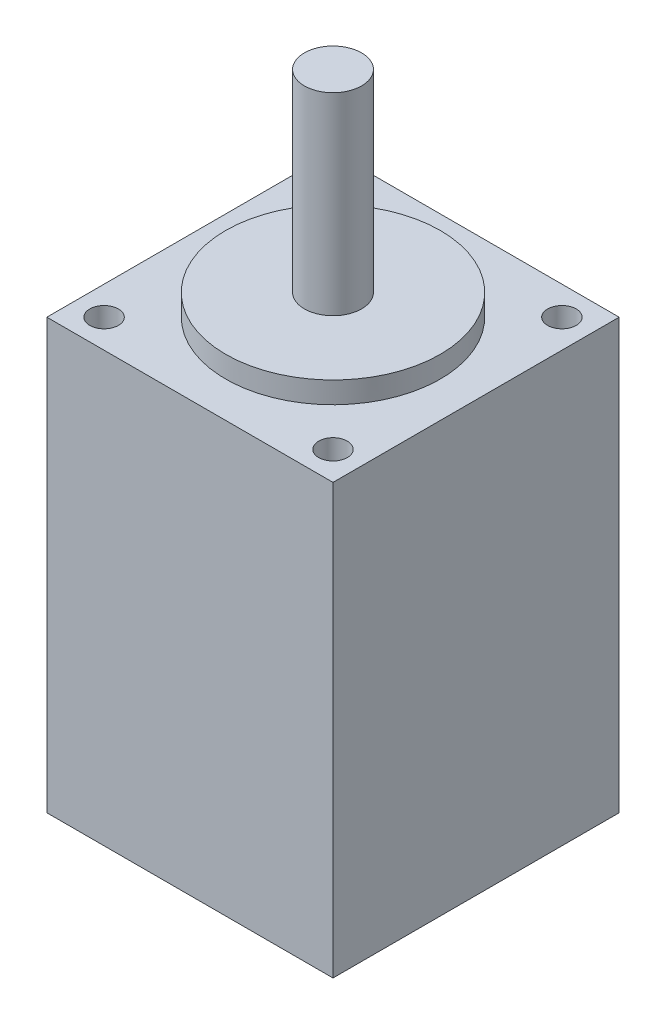
SolidWorks part; units mm, degrees
ref_plane "Front Plane" through (0, 0, 0) normal (0, 0, 1) x (1, 0, 0)
ref_plane "Top Plane" through (0, 0, 0) normal (0, 1, 0) x (1, 0, 0)
ref_plane "Right Plane" through (0, 0, 0) normal (1, 0, 0) x (0, 0, -1)
sketch "Sketch1" plane through (0, 0, 0) normal (0, 1, 0) x (1, 0, 0)
  line L1 (0, 0) -> (20, 0)
  line L2 (0, 0) -> (0, 20)
  line L3 (0, 20) -> (20, 20)
  line L4 (20, 0) -> (20, 20)
  dimension "D1" = 20
extrude "Boss-Extrude1" add sketch "Sketch1" along normal blind 30
sketch "Sketch2" plane through (0, 30, 0) normal (0, 1, 0) x (1, 0, 0)
  line L0 (10, 20) -> (10, 0) construction
  line L1 (20, 20) -> (0, 20) construction
  line L2 (0, 0) -> (20, 0) construction
  line L3 (0, 10) -> (20, 10) construction
  line L4 (0, 20) -> (0, 0) construction
  line L5 (20, 0) -> (20, 20) construction
  line L6 (2, 2) -> (10, 2) construction
  line L7 (2, 18) -> (10, 18) construction
  line L8 (18, 2) -> (18, 10) construction
  line L9 (18, 18) -> (18, 10) construction
  line L10 (18, 18) -> (10, 18) construction
  line L11 (2, 2) -> (2, 10) construction
  line L12 (2, 18) -> (2, 10) construction
  line L13 (18, 2) -> (10, 2) construction
  circle A0 centre (2, 18) radius 1
  circle A1 centre (18, 18) radius 1
  circle A2 centre (18, 2) radius 1
  circle A3 centre (2, 2) radius 1
  dimension "D2" = 2
  dimension "D1" = 16
extrude "Cut-Extrude1" cut sketch "Sketch2" against normal blind 3.5
sketch "Sketch3" plane through (0, 30, 0) normal (0, 1, 0) x (1, 0, 0)
  line L0 (0, 10) -> (20, 10) construction
  line L1 (0, 20) -> (0, 0) construction
  line L2 (20, 0) -> (20, 20) construction
  circle A0 centre (10, 10) radius 7.5
  dimension "D1" = 15
extrude "Boss-Extrude2" add sketch "Sketch3" along normal blind 1.5
sketch "Sketch4" plane through (0, 31.5, 0) normal (0, 1, 0) x (1, 0, 0)
  line L0 (2.5, 10) -> (17.5, 10) construction
  circle A0 centre (10, 10) radius 7.5 construction
  circle A1 centre (10, 10) radius 2
  dimension "D1" = 4
extrude "Boss-Extrude3" add sketch "Sketch4" along normal blind 13.5
